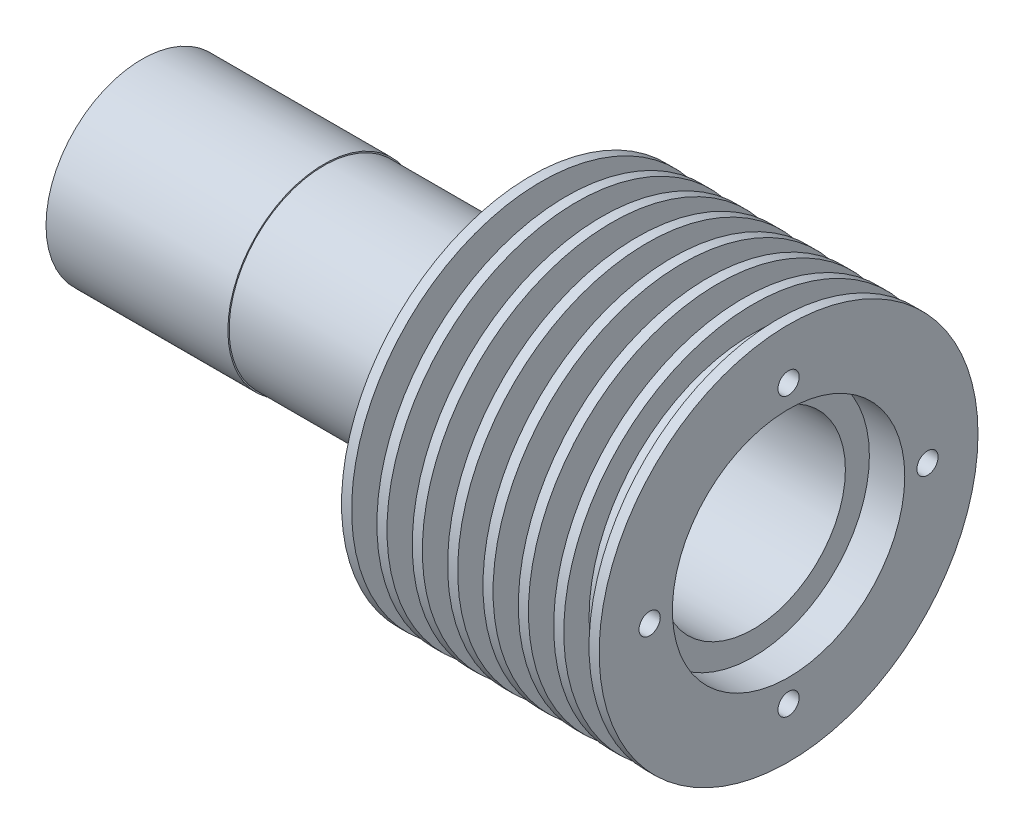
SolidWorks part; units mm, degrees
ref_plane "Front Plane" through (0, 0, 0) normal (0, 0, 1) x (1, 0, 0)
ref_plane "Top Plane" through (0, 0, 0) normal (0, 1, 0) x (1, 0, 0)
ref_plane "Right Plane" through (0, 0, 0) normal (1, 0, 0) x (0, 0, -1)
sketch "Sketch1" plane through (0, 0, 0) normal (0, 0, 1) x (1, 0, 0)
  line L0 (0, 0) -> (-128, 0) construction
  line L1 (-128, 18.25) -> (-128, 19)
  line L2 (-128, 18.25) -> (-92, 18.25)
  line L3 (-128, 19) -> (-92, 19)
  line L4 (-56, 18.75) -> (-51, 18.75)
  line L5 (-51, 18.75) -> (-51, 37.5)
  line L6 (-51, 37.5) -> (-49, 37.5)
  line L7 (-49, 37.5) -> (-49, 18.75)
  line L9 (-44, 18.75) -> (-44, 37.5)
  line L10 (-42, 37.5) -> (-42, 18.75)
  line L11 (-14, 18.75) -> (-9, 18.75)
  line L12 (-37, 18.75) -> (-37, 37.5)
  line L13 (-35, 37.5) -> (-35, 18.75)
  line L15 (-30, 18.75) -> (-30, 37.5)
  line L16 (-28, 37.5) -> (-28, 18.75)
  line L18 (-23, 18.75) -> (-23, 37.5)
  line L19 (-21, 37.5) -> (-21, 18.75)
  line L21 (-16, 18.75) -> (-16, 37.5)
  line L22 (-14, 37.5) -> (-14, 18.75)
  line L24 (-49, 18.75) -> (-44, 18.75) construction
  line L25 (-49, 18.75) -> (-44, 18.75)
  line L26 (-42, 18.75) -> (-37, 18.75)
  line L27 (-35, 18.75) -> (-30, 18.75)
  line L28 (-28, 18.75) -> (-23, 18.75)
  line L29 (-21, 18.75) -> (-16, 18.75)
  line L30 (-92, 19) -> (-92, 18.25)
  line L31 (-9, 18.25) -> (-9, 37.5)
  line L32 (-9, 37.5) -> (-7, 37.5)
  line L33 (-7, 37.5) -> (-7, 32.5)
  line L34 (-7, 32.5) -> (-2, 32.5)
  line L35 (-2, 32.5) -> (-2, 37.5)
  line L36 (-2, 37.5) -> (0, 37.5)
  line L37 (0, 37.5) -> (0, 23)
  line L38 (0, 23) -> (-7, 23)
  line L39 (-7, 23) -> (-7, 18.25)
  line L40 (-7, 18.25) -> (-9, 18.25)
  line L41 (-92, 18.75) -> (-56, 18.75)
  line L42 (-92, 18.25) -> (-9, 18.25)
  line L43 (-44, 37.5) -> (-42, 37.5)
  line L44 (-37, 37.5) -> (-35, 37.5)
  line L45 (-30, 37.5) -> (-28, 37.5)
  line L46 (-23, 37.5) -> (-21, 37.5)
  line L47 (-16, 37.5) -> (-14, 37.5)
  dimension "D1" = 128
  dimension "D2" = 36
  dimension "D3" = 36
  dimension "D4" = 7
  dimension "D5" = 2
  dimension "D6" = 36.5
  dimension "D7" = 75
  dimension "D9" = 65
  dimension "D10" = 2
  dimension "D11" = 9
  dimension "D12" = 7
  dimension "D13" = 46
  dimension "D14" = 38
  dimension "D15" = 37.5
  dimension "D8" = 6
revolve "Revolve1" add sketch "Sketch1" angle 360 about L0
hole_wizard "M5x0.8 Tapped Hole3" positions "Sketch5" profile "Sketch6" tap size "M5x0.8" standard "ANSI Metric"
sketch "Sketch5" plane through (0, 0, 0) normal (1, 0, 0) x (0, 0, -1)
  circle A0 centre (0, 0) radius 27.5 construction
  point P0 (0, 27.5)
  point P8 (-27.5, 0)
  point P10 (0, -27.5)
  point P12 (27.5, 0)
  dimension "D1" = 55
sketch "Sketch6" plane through (0, 27.5, 0) normal (0, 1, 0) x (0, 0, -1)
  line L0 (0, 0) -> (0, 9)
  line L1 (0, 9) -> (2.1, 9)
  line L2 (2.1, 9) -> (2.1, 0)
  line L5 (2.1, 0) -> (0, 0)
  line L11 (0, -6.35) -> (0, 107.95) construction
  dimension "Thru Tap Drill Dia." = 4.2
  dimension "Thru Tap Drill Depth" = 9
